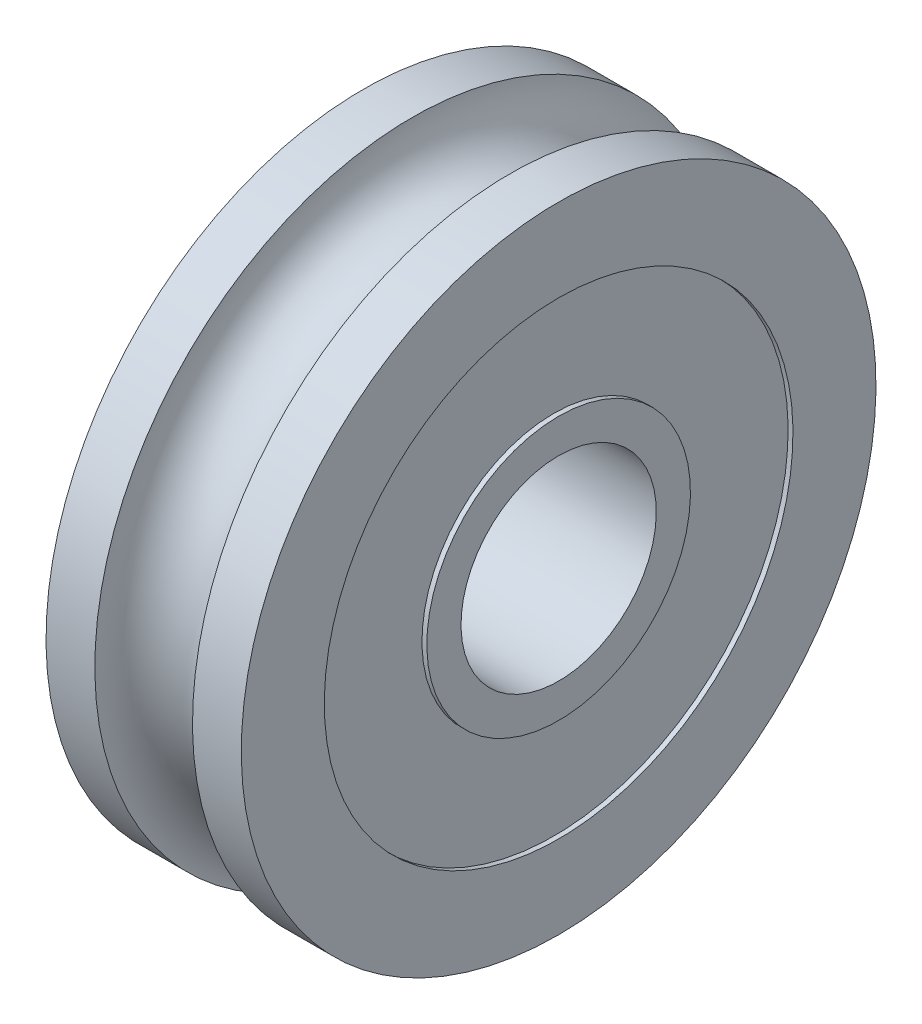
SolidWorks part; units mm, degrees
ref_plane "Front Plane" through (0, 0, 0) normal (0, 0, 1) x (1, 0, 0)
ref_plane "Top Plane" through (0, 0, 0) normal (0, 1, 0) x (1, 0, 0)
ref_plane "Right Plane" through (0, 0, 0) normal (1, 0, 0) x (0, 0, -1)
sketch "Sketch1" plane through (0, 0, 0) normal (0, 0, 1) x (1, 0, 0)
  line L0 (1, 6.5) -> (2, 6.5)
  line L1 (2, 6.5) -> (2, 0)
  line L2 (-1, 6.5) -> (-2, 6.5)
  line L3 (-2, 6.5) -> (-2, 0)
  line L4 (-2, 0) -> (2, 0)
  line L5 (2, 0) -> (4.3185, 0) construction
  arc A0 (-1, 6.5) -> (1, 6.5) centre (0, 6.5) ccw
  point P5 (0, 0)
  dimension "D1" = 13
  dimension "D2" = 4
  dimension "D3" = 1
revolve "Revolve1" add sketch "Sketch1" angle 360 about L5
sketch "Sketch2" plane through (2, 0, 0) normal (1, 0, 0) x (0, 0, -1)
  circle A0 centre (0, 0) radius 2
  dimension "D1" = 4
extrude "Cut-Extrude1" cut sketch "Sketch2" against normal through all
sketch "Sketch3" plane through (2, 0, 0) normal (1, 0, 0) x (0, 0, -1)
  circle A0 centre (0, 0) radius 2.7
  circle A1 centre (0, 0) radius 4.8
  circle A2 centre (0, 0) radius 2 construction
  circle A3 centre (0, 0) radius 6.5 construction
  dimension "D1" = 0.7
  dimension "D2" = 1.7
extrude "Cut-Extrude2" cut sketch "Sketch3" against normal blind 0.1
mirror "Mirror1" about plane through (0, 0, 0) normal (1, 0, 0) of "Cut-Extrude2"
